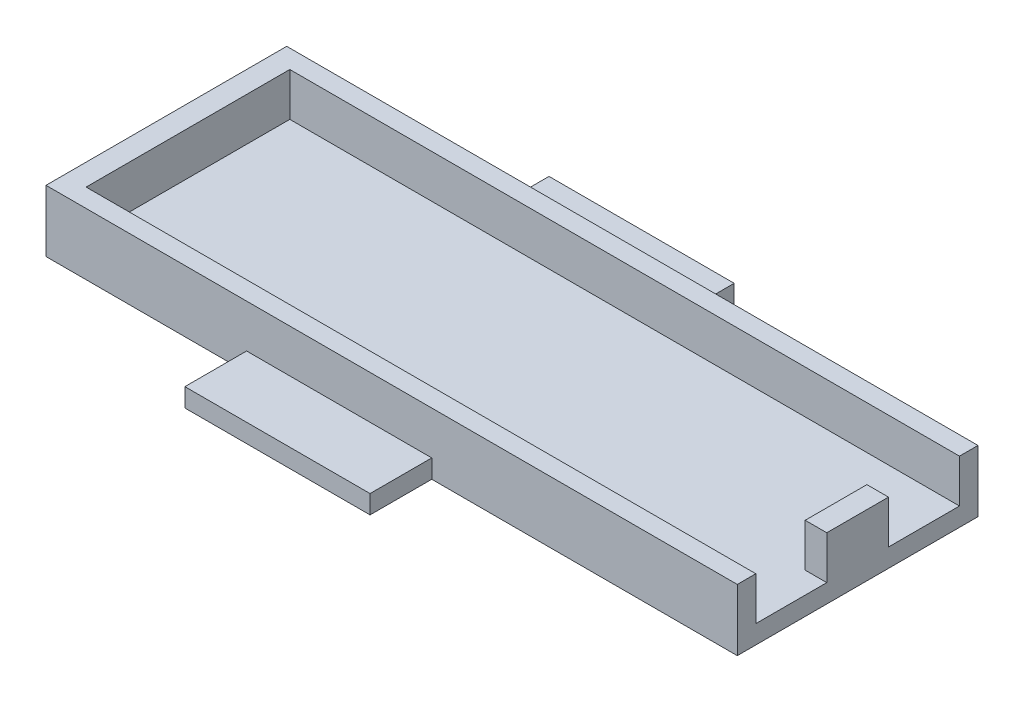
SolidWorks part; units mm, degrees
ref_plane "Front Plane" through (0, 0, 0) normal (0, 0, 1) x (1, 0, 0)
ref_plane "Top Plane" through (0, 0, 0) normal (0, 1, 0) x (1, 0, 0)
ref_plane "Right Plane" through (0, 0, 0) normal (1, 0, 0) x (0, 0, -1)
sketch "Sketch1" plane through (0, 0, 0) normal (0, 1, 0) x (1, 0, 0)
  line L1 (-56, -19.5) -> (56, -19.5)
  line L2 (-56, -19.5) -> (-56, 19.5)
  line L3 (-56, 19.5) -> (56, 19.5)
  line L4 (56, -19.5) -> (56, 19.5)
  line L5 (-56, -19.5) -> (56, 19.5) construction
  line L6 (-56, 19.5) -> (56, -19.5) construction
  line L7 (-52.5, -16.5) -> (52.5, -16.5)
  line L8 (-52.5, -16.5) -> (-52.5, 16.5)
  line L9 (-52.5, 16.5) -> (52.5, 16.5)
  line L10 (52.5, -16.5) -> (52.5, 16.5)
  line L11 (-52.5, -16.5) -> (52.5, 16.5) construction
  line L12 (-52.5, 16.5) -> (52.5, -16.5) construction
  point P0 (0, 0)
  point P6 (0, 0)
  dimension "D1" = 112
  dimension "D2" = 39
  dimension "D3" = 105
  dimension "D4" = 33
extrude "Boss-Extrude1" add sketch "Sketch1" along normal blind 10
sketch "Sketch2" plane through (0, 0, 0) normal (0, 1, 0) x (1, 0, 0)
  line L1 (-52.5, -16.5) -> (52.5, -16.5)
  line L2 (-52.5, -16.5) -> (-52.5, 16.5)
  line L3 (-52.5, 16.5) -> (52.5, 16.5)
  line L4 (52.5, -16.5) -> (52.5, 16.5)
  line L5 (-52.5, -16.5) -> (52.5, 16.5) construction
  line L6 (-52.5, 16.5) -> (52.5, -16.5) construction
  point P0 (0, 0)
extrude "Boss-Extrude2" add sketch "Sketch2" along normal blind 3
sketch "Sketch3" plane through (52.5, 0, 0) normal (-1, 0, 0) x (0, 0, 1)
  line L0 (-19.5, 10) -> (-19.5, 0) construction
  line L1 (-16.5, 13.9192) -> (-5, 13.9192)
  line L2 (-16.5, 13.9192) -> (-16.5, 3)
  line L3 (-16.5, 3) -> (-5, 3)
  line L4 (-5, 13.9192) -> (-5, 3)
  line L5 (5, 14.0513) -> (16.5, 14.0513)
  line L6 (5, 14.0513) -> (5, 3)
  line L7 (5, 3) -> (16.5, 3)
  line L8 (16.5, 14.0513) -> (16.5, 3)
  line L9 (-19.5, 0) -> (19.5, 0) construction
  line L10 (19.5, 10) -> (19.5, 0) construction
  line L11 (21.45, 0) -> (-21.45, 0) construction
  line L12 (0, -5.5) -> (0, 5.5) construction
  dimension "D1" = 3
  dimension "D2" = 3
  dimension "D3" = 3
  dimension "D4" = 3
  dimension "D5" = 5
  dimension "D6" = 5
extrude "Cut-Extrude1" cut sketch "Sketch3" against normal through all
sketch "Sketch4" plane through (0, 0, 0) normal (0, 1, 0) x (1, 0, 0)
  line L0 (56, 19.5) -> (-56, 19.5) construction
  line L1 (-23.5, 19.5) -> (6.5, 19.5)
  line L2 (-23.5, 19.5) -> (-23.5, 29.5)
  line L3 (-23.5, 29.5) -> (6.5, 29.5)
  line L4 (6.5, 19.5) -> (6.5, 29.5)
  line L5 (-5.5, 0) -> (5.5, 0) construction
  line L6 (-23.5, -29.5) -> (6.5, -29.5)
  line L7 (6.5, -19.5) -> (6.5, -29.5)
  line L8 (-23.5, -19.5) -> (6.5, -19.5)
  line L9 (-23.5, -19.5) -> (-23.5, -29.5)
  line L10 (-56, 19.5) -> (-56, -19.5) construction
  dimension "D1" = 30
  dimension "D2" = 10
  dimension "D3" = 32.5
extrude "Boss-Extrude3" add sketch "Sketch4" along normal blind 3
sketch "Sketch5" plane through (0, 0, 0) normal (0, -1, 0) x (1, 0, 0)
  line L0 (-23.5, 29.5) -> (6.5, 29.5) construction
  line L1 (-16.5, 26.3459) -> (0.5, 26.3459)
  line L2 (-16.5, 26.3459) -> (-16.5, 23.3459)
  line L3 (-16.5, 23.3459) -> (0.5, 23.3459)
  line L4 (0.5, 26.3459) -> (0.5, 23.3459)
  line L5 (-56, 19.5) -> (-23.5, 19.5) construction
  line L6 (-56, -19.5) -> (-56, 19.5) construction
  arc A0 (0.5, 26.3459) -> (0.5, 23.3459) centre (0.5, 24.8459) cw
  arc A1 (-16.5, 26.3459) -> (-16.5, 23.3459) centre (-16.5, 24.8459) ccw
  point P6 (-18, 24.8459)
  point P7 (2, 24.8459)
  point P10 (-8.5, 29.5)
  point P11 (-8, 26.3459)
  point P12 (-53, 19.5)
  dimension "D1" = 20
  dimension "D2" = 3
  dimension "D3" = 3
  dimension "D4" = 35
extrude "Boss-Extrude4" add sketch "Sketch5" along normal blind 3 contours L4 L1 L2 L3 | L2 A1 | A0 L4
mirror "Mirror1" about plane through (0, 0, 0) normal (0, 0, 1) of "Boss-Extrude4"
